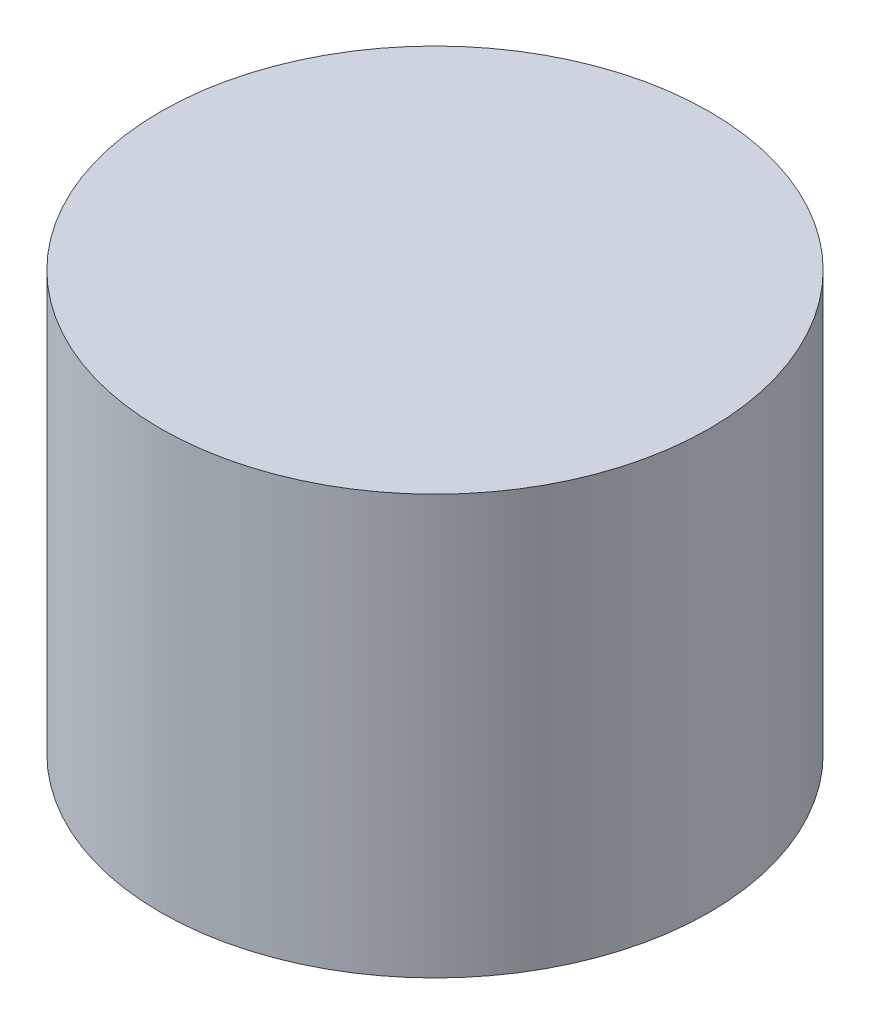
SolidWorks part; units mm, degrees
ref_plane "Front Plane" through (0, 0, 0) normal (0, 0, 1) x (1, 0, 0)
ref_plane "Top Plane" through (0, 0, 0) normal (0, 1, 0) x (1, 0, 0)
ref_plane "Right Plane" through (0, 0, 0) normal (1, 0, 0) x (0, 0, -1)
sketch "Sketch1" plane through (0, 0, 0) normal (0, 1, 0) x (1, 0, 0)
  circle A0 centre (0, 0) radius 19
  dimension "D1" = 38
extrude "Boss-Extrude1" add sketch "Sketch1" along normal blind 29
